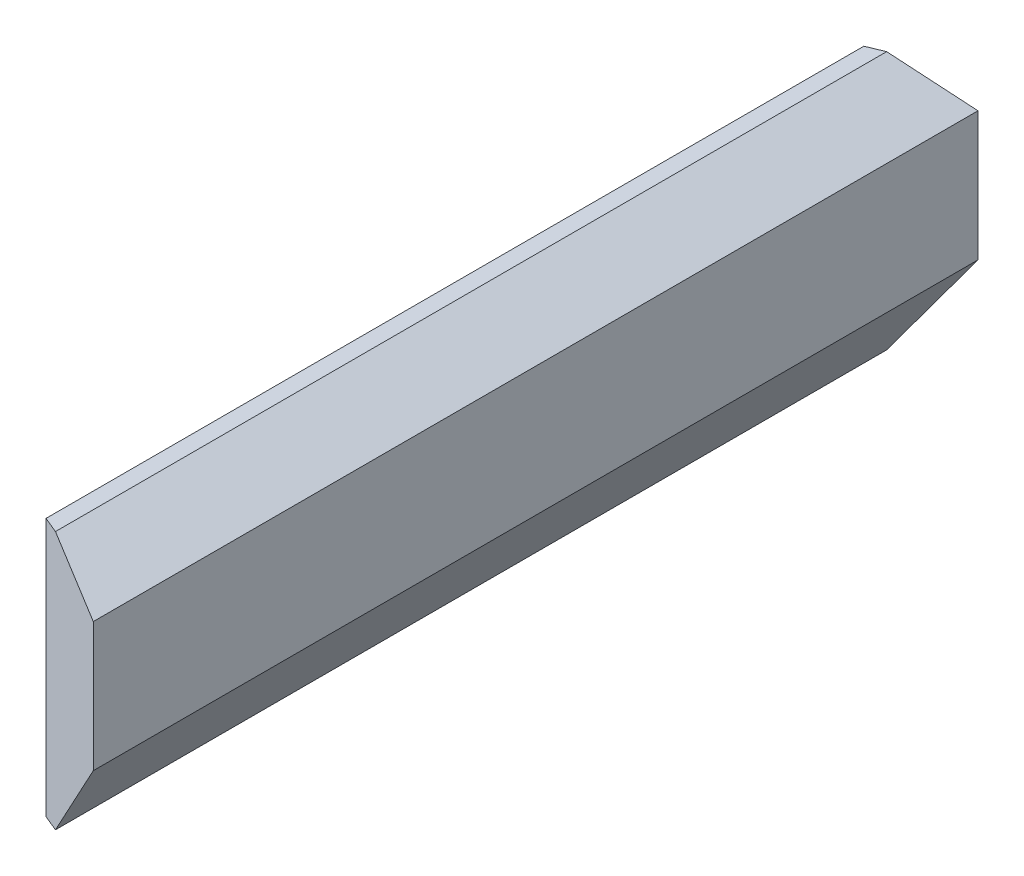
SolidWorks part; units mm, degrees
material "橡胶"
ref_plane "前视基准面" through (0, 0, 0) normal (0, 0, 1) x (1, 0, 0)
ref_plane "上视基准面" through (0, 0, 0) normal (0, 1, 0) x (1, 0, 0)
ref_plane "右视基准面" through (0, 0, 0) normal (1, 0, 0) x (0, 0, -1)
sketch "草图1" plane through (0, 0, 0) normal (0, 0, 1) x (1, 0, 0)
  line L0 (0, 0) -> (0, 80)
  line L1 (0, 80) -> (5, 80)
  line L2 (5, 80) -> (25, 70)
  line L3 (25, 70) -> (25, 30)
  line L4 (25, 30) -> (5, 0)
  line L5 (5, 0) -> (0, 0)
  dimension "D1" = 80
  dimension "D2" = 25
  dimension "D3" = 40
  dimension "D4" = 10
  dimension "D5" = 5
extrude "拉伸1" add sketch "草图1" along normal blind 300
sketch "草图2" plane through (0, 80, 0) normal (0, 1, 0) x (-1, 0, 0)
  line L0 (0, 276.65) -> (-136.8165, 333.3213)
  line L1 (0, 300) -> (0, 0) construction
  line L2 (-136.8165, 333.3213) -> (0, 333.3213)
  line L3 (0, 333.3213) -> (0, 276.65)
  line L4 (0, 0) -> (0, 23.35)
  line L5 (0, 23.35) -> (-107.5282, -21.1896)
  line L6 (-107.5282, -21.1896) -> (0, -21.1896)
  line L7 (0, -21.1896) -> (0, 0)
  line L8 (0, 150) -> (111.0571, 150) construction
  dimension "D1" = 253.3
  dimension "D2" = 112.5
  dimension "D3" = 112.5
extrude "切除-拉伸1" cut sketch "草图2" against normal blind 290
ref_plane "对中面" through (0, 0, 150) normal (0, 0, 1) x (1, 0, 0)
sketch "草图4" plane through (0, 0, 0) normal (-1, 0, 0) x (0, 0, 1)
  line L0 (150, 80) -> (150, -13.2007) construction
  line L1 (28.35, 75) -> (271.65, 75)
  line L2 (28.35, 75) -> (28.35, 5)
  line L3 (28.35, 5) -> (271.65, 5)
  line L4 (271.65, 75) -> (271.65, 5)
  line L5 (276.65, 80) -> (23.35, 80) construction
  line L6 (150, -13.75) -> (150, 13.75) construction
  line L7 (23.35, 0) -> (23.35, 80) construction
  line L8 (81.35, 75) -> (86.35, 75)
  line L9 (81.35, 75) -> (81.35, 5)
  line L10 (81.35, 5) -> (86.35, 5)
  line L11 (86.35, 75) -> (86.35, 5)
  line L12 (213.65, 75) -> (218.65, 75)
  line L13 (213.65, 75) -> (213.65, 5)
  line L14 (213.65, 5) -> (218.65, 5)
  line L15 (218.65, 75) -> (218.65, 5)
  line L16 (23.35, 40) -> (298.5499, 40) construction
  line L19 (144.35, 75) -> (155.65, 75)
  line L20 (144.35, 75) -> (144.35, 5)
  line L21 (144.35, 5) -> (155.65, 5)
  line L22 (155.65, 75) -> (155.65, 5)
  dimension "D1" = 5
  dimension "D2" = 5
  dimension "D3" = 5
  dimension "D4" = 5
  dimension "D5" = 53
  dimension "D6" = 58
ref_plane "基准面4" through (0, 0, 28.35) normal (0, 0, 1) x (1, 0, 0)
ref_plane "基准面5" through (0, 0, 86.35) normal (0, 0, 1) x (1, 0, 0)
ref_plane "基准面6" through (0, 0, 213.65) normal (0, 0, 1) x (1, 0, 0)
ref_plane "基准面8" through (0, 0, 218.65) normal (0, 0, 1) x (1, 0, 0)
sketch "草图5" plane through (0, 0, 28.35) normal (0, 0, 1) x (1, 0, 0)
  line L0 (0, 75) -> (6.0557, 75)
  line L1 (0, 75) -> (0, 5) construction
  line L2 (0, 80) -> (0, -13.2007) construction
  line L3 (6.0557, 75) -> (21, 67.5279)
  line L4 (21, 67.5279) -> (21, 31.2111)
  line L5 (21, 31.2111) -> (3.5259, 5)
  line L6 (3.5259, 5) -> (0, 5)
  line L7 (0, 5) -> (0, 75)
  line L8 (25, 30) -> (5, 0) construction
  line L9 (5, 80) -> (25, 70) construction
  line L10 (5, 80) -> (0, 80) construction
  line L11 (25, 70) -> (25, 30) construction
  line L12 (5, 0) -> (0, 0) construction
  dimension "D1" = 5
  dimension "D2" = 4
  dimension "D3" = 4
  dimension "D4" = 4
  dimension "D5" = 5
extrude "切除-拉伸3" cut sketch "草图5" along normal blind 53
sketch "草图6" plane through (0, 0, 86.35) normal (0, 0, 1) x (1, 0, 0)
  line L0 (0, 75) -> (6.0557, 75)
  line L1 (6.0557, 75) -> (21, 67.5279)
  line L2 (21, 67.5279) -> (21, 31.2111)
  line L3 (21, 31.2111) -> (3.5259, 5)
  line L4 (3.5259, 5) -> (0, 5)
  line L5 (0, 5) -> (0, 75)
extrude "切除-拉伸4" cut sketch "草图6" along normal blind 60
sketch "草图7" plane through (0, 0, 218.65) normal (0, 0, 1) x (1, 0, 0)
  line L0 (0, 75) -> (6.0557, 75)
  line L1 (6.0557, 75) -> (21, 67.5279)
  line L2 (21, 67.5279) -> (21, 31.2111)
  line L3 (21, 31.2111) -> (21, 67.5279) construction
  line L4 (3.5259, 5) -> (21, 31.2111) construction
  line L5 (21, 31.2111) -> (3.5259, 5)
  line L6 (3.5259, 5) -> (0, 5)
  line L7 (0, 5) -> (0, 75)
extrude "切除-拉伸5" cut sketch "草图7" along normal blind 53
sketch "草图8" plane through (0, 0, 213.65) normal (0, 0, 1) x (1, 0, 0)
  line L0 (0, 75) -> (6.0557, 75)
  line L1 (6.0557, 75) -> (21, 67.5279)
  line L2 (21, 67.5279) -> (21, 31.2111)
  line L3 (21, 31.2111) -> (3.5259, 5)
  line L4 (3.5259, 5) -> (0, 5)
  line L5 (0, 5) -> (0, 75)
extrude "切除-拉伸6" cut sketch "草图8" against normal blind 60
